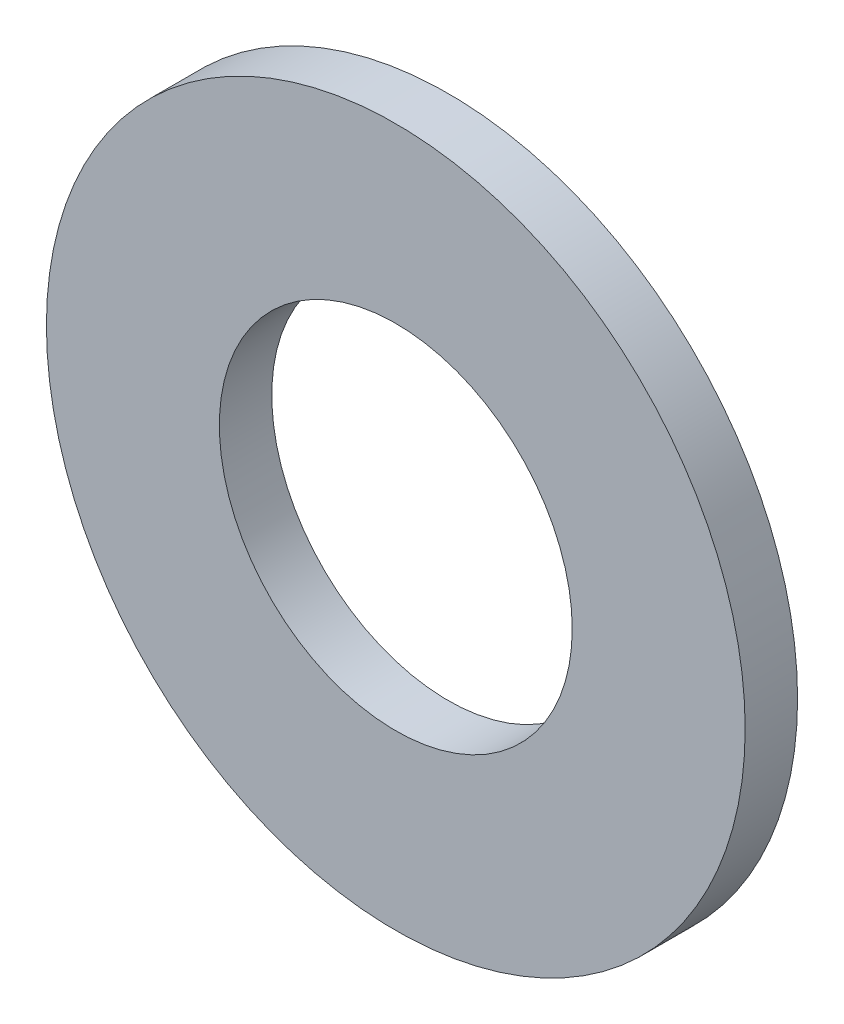
SolidWorks part; units mm, degrees
ref_plane "Front Plane" through (0, 0, 0) normal (0, 0, 1) x (1, 0, 0)
ref_plane "Top Plane" through (0, 0, 0) normal (0, 1, 0) x (1, 0, 0)
ref_plane "Right Plane" through (0, 0, 0) normal (1, 0, 0) x (0, 0, -1)
sketch "Sketch1" plane through (0, 0, 0) normal (0, 0, 1) x (1, 0, 0)
  circle A0 centre (0, 0) radius 20
  circle A1 centre (0, 0) radius 10.1
  dimension "D1" = 40
  dimension "D2" = 20.2
extrude "Boss-Extrude1" add sketch "Sketch1" along normal mid plane 3
